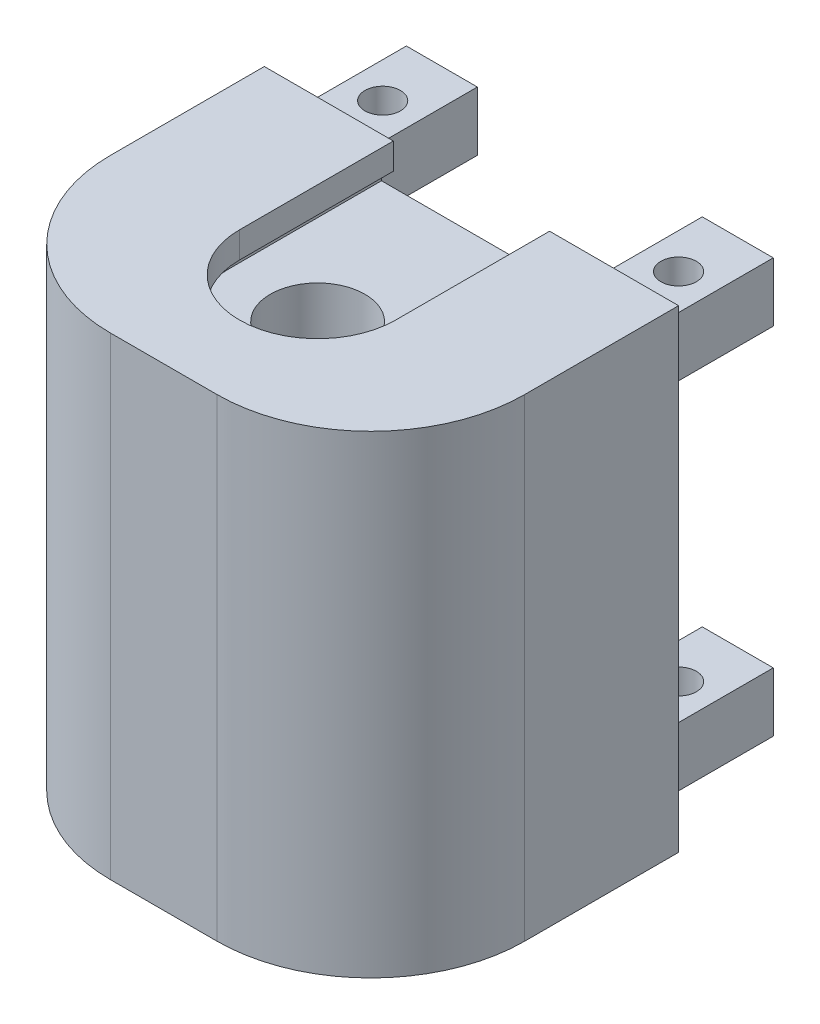
SolidWorks part; units mm, degrees
material "ABS"
ref_plane "Front Plane" through (0, 0, 0) normal (0, 0, 1) x (1, 0, 0)
ref_plane "Top Plane" through (0, 0, 0) normal (0, 1, 0) x (1, 0, 0)
ref_plane "Right Plane" through (0, 0, 0) normal (1, 0, 0) x (0, 0, -1)
sketch "Sketch1" plane through (0, 0, 0) normal (0, 1, 0) x (1, 0, 0)
  line L0 (0, 0) -> (6, 0)
  line L1 (6, 0) -> (6, -10)
  line L2 (6, -10) -> (25, -10)
  line L3 (25, -10) -> (25, 0)
  line L4 (25, 0) -> (31, 0)
  line L5 (31, 0) -> (31, -10)
  line L7 (0, -10) -> (0, 0)
  line L8 (0, -10) -> (-2, -10)
  line L11 (33, -36) -> (33, -10)
  line L12 (33, -10) -> (31, -10)
  line L13 (3, 0) -> (3, -5) construction
  line L14 (15.5, -10) -> (15.5, 0) construction
  line L15 (33, -36) -> (-2, -36)
  line L16 (-2, -36) -> (-2, -10)
  circle A0 centre (3, -5) radius 1.5
  circle A1 centre (28, -5) radius 1.5
  dimension "D9" = 3
  dimension "D1" = 36
  dimension "D2" = 35
  dimension "D3" = 10
  dimension "D4" = 6
  dimension "D5" = 2
  dimension "D6" = 6
  dimension "D7" = 2
  dimension "D8" = 5
sketch "Sketch10" plane through (0, 0, 0) normal (0, 1, 0) x (1, 0, 0)
  line L0 (-2, -36) -> (33, -36)
  line L1 (33, -36) -> (33, -10)
  line L2 (33, -10) -> (-2, -10)
  line L3 (-2, -36) -> (-2, -10)
extrude "Boss-Extrude4" add sketch "Sketch10" along normal blind 2.5
extrude "Boss-Extrude5" add sketch "Sketch1" against normal blind 5
sketch "Sketch11" plane through (0, -5, 0) normal (0, -1, 0) x (1, 0, 0)
  line L0 (-2, 36) -> (-2, 10)
  line L1 (-2, 10) -> (33, 10)
  line L2 (33, 10) -> (33, 36)
  line L3 (33, 36) -> (-2, 36)
extrude "Boss-Extrude6" add sketch "Sketch11" along normal blind 2.5
ref_plane "Plane1" through (0, -2.5, 0) normal (0, 1, 0) x (1, 0, 0)
sketch "Sketch3" plane through (0, 0, 10) normal (0, 0, -1) x (-1, 0, 0)
  line L0 (-22.1, 2.5) -> (-22.1, 0.2875)
  line L2 (-22.1, 0.2875) -> (-23.1, 0.2875)
  line L3 (-23.1, 0.2875) -> (-23.1, -0.9125)
  line L4 (-23.1, -0.9125) -> (-15.5, -0.9125)
  line L5 (-15.5, -0.9125) -> (-7.9, -0.9125)
  line L6 (-7.9, -0.9125) -> (-7.9, 0.2875)
  line L7 (-7.9, 0.2875) -> (-8.9, 0.2875)
  line L8 (-8.9, 0.2875) -> (-8.9, 2.5)
  line L9 (-8.9, 2.5) -> (-22.1, 2.5)
  line L10 (-25, -2.5) -> (-6, -2.5) construction
  line L13 (-15.5, -2.5) -> (-15.5, -0.9125) construction
  line L14 (-33, 2.5) -> (2, 2.5) construction
  line L15 (-6, -5) -> (-6, 0) construction
  line L16 (-25, -5) -> (-25, 0) construction
  dimension "D1" = 1.2
  dimension "D2" = 3.4125
  dimension "D3" = 13.2
  dimension "D4" = 15.2
extrude "Cut-Extrude1" cut sketch "Sketch3" against normal blind 13 and the other way through all
sketch "Sketch4" plane through (0, -0.9125, 0) normal (0, 1, 0) x (1, 0, 0)
  line L1 (23.1, -23) -> (7.9, -23) construction
  circle A0 centre (15.5, -23) radius 7.6
  dimension "D1" = 15.2
extrude "Cut-Extrude2" cut sketch "Sketch4" along normal up to surface (1.2 mm away) up to face at (8.4, 0.2875, 16.5)
sketch "Sketch5" plane through (0, -0.9125, 0) normal (0, 1, 0) x (1, 0, 0)
  line L1 (8.9, -23) -> (22.1, -23) construction
  circle A0 centre (15.5, -23) radius 6.6
  dimension "D1" = 13.2
extrude "Cut-Extrude3" cut sketch "Sketch5" along normal through all
sketch "Sketch12" plane through (0, -7.5, 0) normal (0, -1, 0) x (1, 0, 0)
  line L4 (33, 36) -> (-2, 36)
  line L5 (-2, 36) -> (-2, 10)
  line L6 (-2, 10) -> (33, 10)
  line L7 (33, 10) -> (33, 36)
  line L8 (33, 36) -> (-2, 36)
  line L9 (-2, 36) -> (-2, 10)
  line L10 (-2, 10) -> (33, 10)
  line L11 (33, 10) -> (33, 36)
  dimension "D1" = 0
extrude "Boss-Extrude7" add sketch "Sketch12" along normal blind 15
sketch "Sketch13" plane through (0, -22.5, 0) normal (0, -1, 0) x (1, 0, 0)
  line L4 (33, 10) -> (33, 36)
  line L5 (33, 36) -> (-2, 36)
  line L6 (-2, 36) -> (-2, 10)
  line L7 (-2, 10) -> (33, 10)
  line L8 (33, 10) -> (33, 36)
  line L9 (33, 36) -> (-2, 36)
  line L10 (-2, 36) -> (-2, 10)
  line L11 (-2, 10) -> (33, 10)
  dimension "D1" = 0
extrude "Boss-Extrude8" add sketch "Sketch13" along normal blind 7.5
sketch "Sketch14" plane through (0, -30, 0) normal (0, -1, 0) x (1, 0, 0)
  line L12 (0, 0) -> (6, 0)
  line L13 (6, 0) -> (6, 10)
  line L14 (6, 10) -> (25, 10)
  line L15 (25, 10) -> (25, 0)
  line L16 (25, 0) -> (31, 0)
  line L17 (31, 0) -> (31, 10)
  line L18 (31, 10) -> (33, 10)
  line L19 (33, 10) -> (33, 36)
  line L20 (33, 36) -> (-2, 36)
  line L21 (-2, 36) -> (-2, 10)
  line L22 (-2, 10) -> (0, 10)
  line L23 (0, 10) -> (0, 0)
  line L24 (0, 0) -> (6, 0)
  line L25 (6, 0) -> (6, 10)
  line L26 (6, 10) -> (25, 10)
  line L27 (25, 10) -> (25, 0)
  line L28 (25, 0) -> (31, 0)
  line L29 (31, 0) -> (31, 10)
  line L30 (31, 10) -> (33, 10)
  line L31 (33, 10) -> (33, 36)
  line L32 (33, 36) -> (-2, 36)
  line L33 (-2, 36) -> (-2, 10)
  line L34 (-2, 10) -> (0, 10)
  line L35 (0, 10) -> (0, 0)
  circle A1 centre (3, 5) radius 1.5
  circle A2 centre (3, 5) radius 1.5
  circle A3 centre (28, 5) radius 1.5
  circle A4 centre (28, 5) radius 1.5
  dimension "D1" = 0
  dimension "D2" = 0
  dimension "D3" = 0
extrude "Boss-Extrude9" add sketch "Sketch14" along normal blind 5
sketch "Sketch15" plane through (0, -35, 0) normal (0, -1, 0) x (1, 0, 0)
  line L4 (33, 36) -> (-2, 36)
  line L5 (33, 10) -> (33, 36)
  line L6 (-2, 10) -> (33, 10)
  line L7 (-2, 36) -> (-2, 10)
  line L8 (33, 36) -> (-2, 36)
  line L9 (33, 10) -> (33, 36)
  line L10 (-2, 10) -> (33, 10)
  line L11 (-2, 36) -> (-2, 10)
  dimension "D1" = 0
extrude "Boss-Extrude10" add sketch "Sketch15" along normal blind 2.5
ref_plane "Plane4" through (0, -17.5, 0) normal (0, 1, 0) x (1, 0, 0)
mirror "Mirror8" about plane through (0, -17.5, 0) normal (0, 1, 0) of "Cut-Extrude3", "Cut-Extrude2", "Cut-Extrude1"
sketch "Sketch8" plane through (0, -0.9125, 0) normal (0, 1, 0) x (1, 0, 0)
  circle A0 centre (15.5, -23) radius 4
  dimension "D1" = 8
extrude "Cut-Extrude6" cut sketch "Sketch8" against normal through all
fillet "Fillet1" radius 13 2 edges at (-2, -17.5, 36) (33, -17.5, 36)
